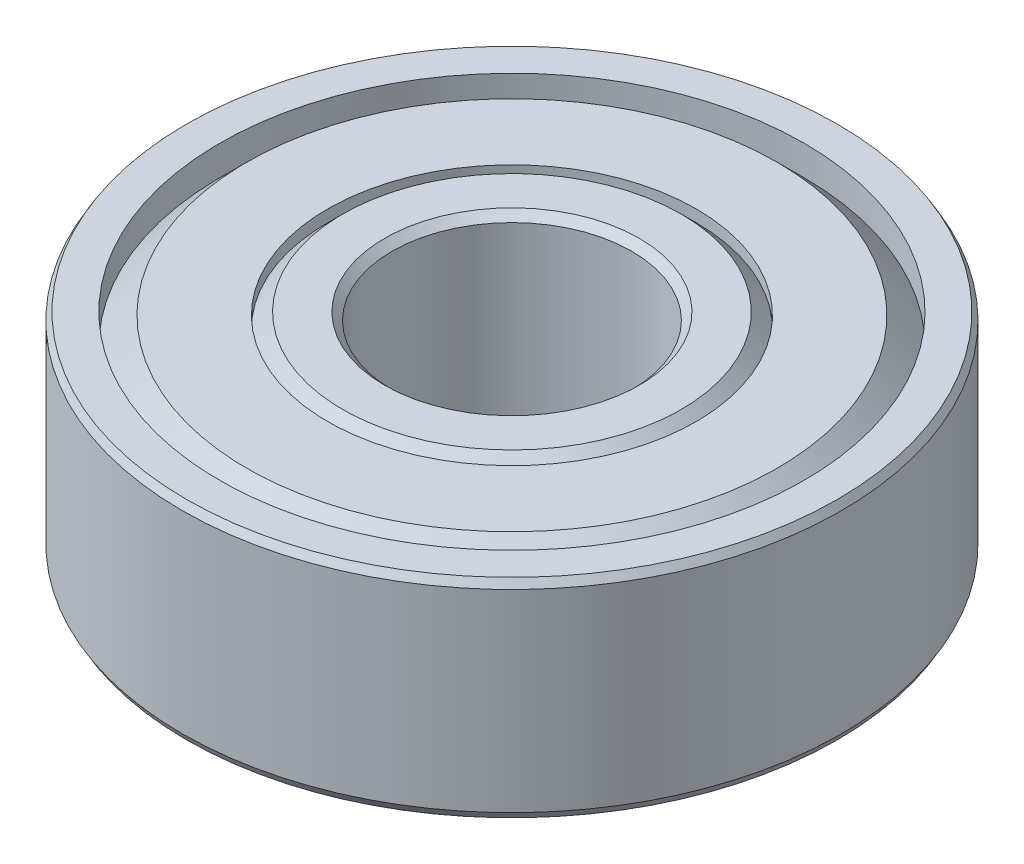
SolidWorks part; units mm, degrees
ref_plane "Alzado" through (0, 0, 0) normal (0, 0, 1) x (1, 0, 0)
ref_plane "Planta" through (0, 0, 0) normal (0, 1, 0) x (1, 0, 0)
ref_plane "Vista lateral" through (0, 0, 0) normal (1, 0, 0) x (0, 0, -1)
sketch "Croquis1" plane through (0, 0, 0) normal (0, 1, 0) x (1, 0, 0)
  circle A0 centre (0, 0) radius 11
  circle A1 centre (0, 0) radius 4
  dimension "D1" = 22
  dimension "D2" = 8
extrude "Saliente-Extruir1" add sketch "Croquis1" along normal blind 6.95
sketch "Croquis2" plane through (0, 0, 0) normal (0, 0, 1) x (1, 0, 0)
  line L0 (0, 0) -> (0, 6.95) construction
  line L1 (-9.75, 6.95) -> (-9.75, 5.95)
  line L2 (11, 6.95) -> (-11, 6.95) construction
  line L3 (-9.75, 5.95) -> (-8.85, 6.85)
  line L4 (0, 3.475) -> (-14.6822, 3.475) construction
  line L5 (-6.15, 6.85) -> (-6.15, 6.45)
  line L6 (-6.15, 6.45) -> (-5.65, 6.95)
  line L7 (-5.65, 6.95) -> (-9.75, 6.95)
  line L8 (-8.85, 6.85) -> (-6.15, 6.85)
  line L9 (4, 6.95) -> (-4, 6.95) construction
  line L10 (-8.85, 0.1) -> (-6.15, 0.1)
  line L11 (-5.65, 0) -> (-9.75, 0)
  line L12 (-6.15, 0.5) -> (-5.65, 0)
  line L13 (-6.15, 0.1) -> (-6.15, 0.5)
  line L14 (-9.75, 1) -> (-8.85, 0.1)
  line L15 (-9.75, 0) -> (-9.75, 1)
  dimension "D1" = 12.3
  dimension "D2" = 45
  dimension "D3" = 0.1
  dimension "D4" = 0.5
  dimension "D5" = 19.5
  dimension "D6" = 45
  dimension "D7" = 1
revolve "Cortar-Revolución1" cut sketch "Croquis2" angle 360 about L0
chamfer "Chaflán1" distance 0.25 angle 45 2 edges at (0, 6.95, 4) (0, 0, 4)
chamfer "Chaflán2" distance 0.25 angle 30 2 edges at (0, 6.95, 11) (0, 0, 11)
